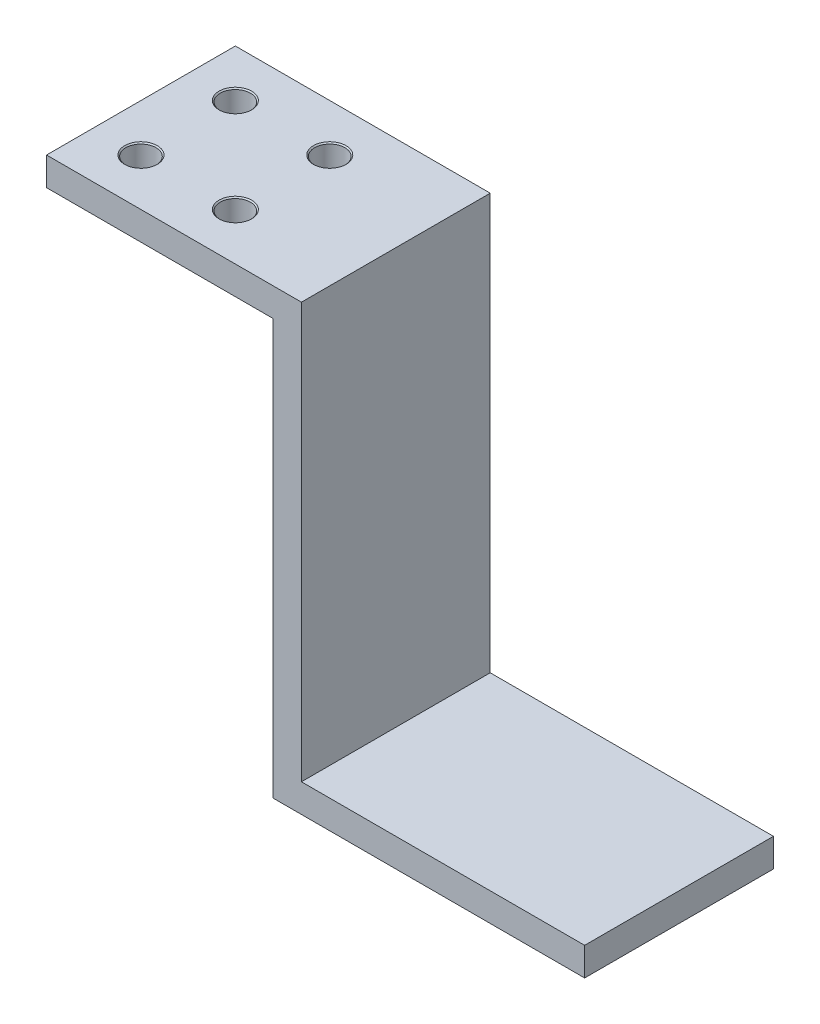
SolidWorks part; units mm, degrees
ref_plane "Front Plane" through (0, 0, 0) normal (0, 0, 1) x (1, 0, 0)
ref_plane "Top Plane" through (0, 0, 0) normal (0, 1, 0) x (1, 0, 0)
ref_plane "Right Plane" through (0, 0, 0) normal (1, 0, 0) x (0, 0, -1)
sketch "Sketch1" plane through (0, 0, 0) normal (0, 0, 1) x (1, 0, 0)
  line L0 (0, 44) -> (24, 44)
  line L1 (24, 44) -> (24, 0)
  line L2 (24, 0) -> (57, 0)
  line L3 (57, 0) -> (57, 3)
  line L4 (57, 3) -> (27, 3)
  line L5 (27, 3) -> (27, 47)
  line L6 (27, 47) -> (0, 47)
  line L7 (0, 47) -> (0, 44)
  line L8 (24, 25) -> (27, 25) construction
  point P11 (0, 0)
  point P12 (27, 25)
  point P13 (0, 0)
  dimension "D1" = 3
  dimension "D2" = 24
  dimension "D3" = 44
  dimension "D4" = 30
extrude "Boss-Extrude1" add sketch "Sketch1" along normal blind 20
hole_wizard "M3 Clearance Hole1" positions "Sketch2" profile "Sketch3" hole size "M3" standard "ANSI Metric" end condition through all
sketch "Sketch2" plane through (0, 47, 0) normal (0, 1, 0) x (1, 0, 0)
  line L0 (0, -10) -> (20, -10) construction
  line L1 (0, -20) -> (0, 0) construction
  line L4 (10, 0) -> (10, -20) construction
  line L7 (24, -20) -> (24, 0) construction
  line L8 (24, -20) -> (24, 0) construction
  line L9 (27, -20) -> (0, -20) construction
  point P17 (5, -5)
  point P25 (5, -15)
  point P26 (15, -5)
  point P27 (15, -15)
  point P34 (20, -10)
  point P35 (11.5, -1.7858)
  point P36 (0, 0)
  point P37 (10, -10)
  point P38 (10, -20)
  point P41 (0, 0)
  dimension "D1" = 5
  dimension "D2" = 5
  dimension "D3" = 20
sketch "Sketch3" plane through (15, 47, 15) normal (1, 0, 0) x (0, 0, 1)
  line L0 (0, 0) -> (0, 47)
  line L1 (0, 47) -> (1.6, 47)
  line L2 (1.6, 47) -> (1.6, 0.125)
  line L3 (1.6, 0.125) -> (1.725, 0)
  line L5 (1.725, 0) -> (0, 0)
  line L6 (-1.6, 0.125) -> (-1.725, 0) construction
  line L11 (0, -6.35) -> (0, 107.95) construction
  dimension "Thru Hole Dia." = 3.2
  dimension "Thru Hole Depth" = 47
  dimension "Near C'Sink Dia." = 3.45
  dimension "Near C'Sink Angle" = 90
